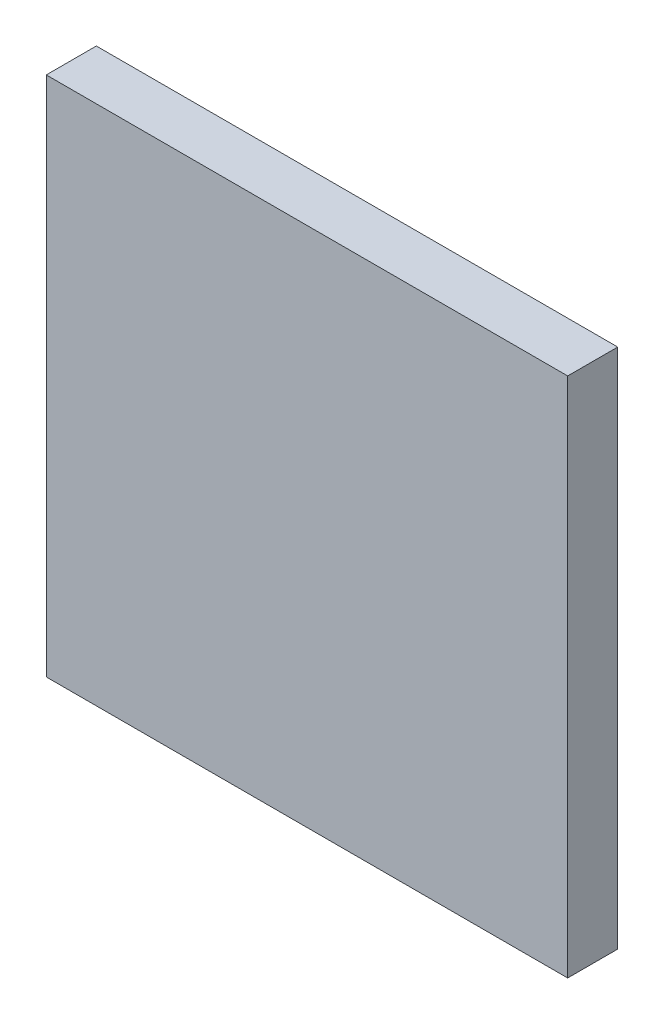
SolidWorks part; units mm, degrees
ref_plane "Front Plane" through (0, 0, 0) normal (0, 0, 1) x (1, 0, 0)
ref_plane "Top Plane" through (0, 0, 0) normal (0, 1, 0) x (1, 0, 0)
ref_plane "Right Plane" through (0, 0, 0) normal (1, 0, 0) x (0, 0, -1)
sketch "Sketch1" plane through (0, 0, 0) normal (0, 0, 1) x (1, 0, 0)
  line L1 (0, 0) -> (50, 0)
  line L2 (0, 0) -> (0, 50)
  line L3 (0, 50) -> (50, 50)
  line L4 (50, 0) -> (50, 50)
  dimension "D1" = 50
  dimension "D2" = 50
extrude "Boss-Extrude1" add sketch "Sketch1" along normal blind 4.8
